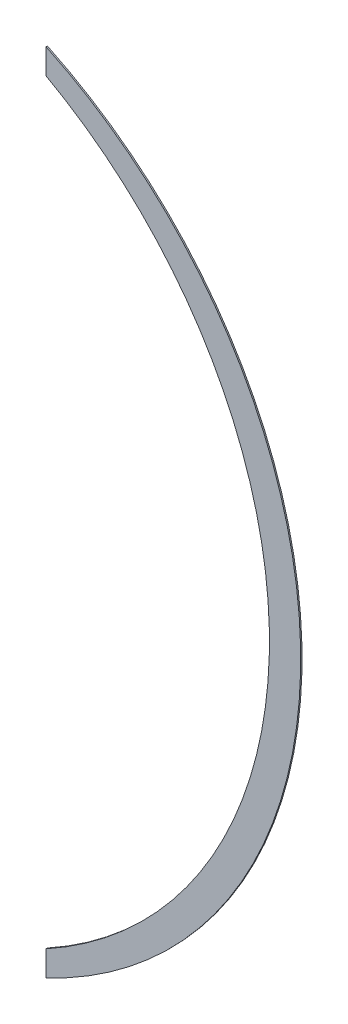
SolidWorks part; units mm, degrees
material "ASTM A36 Steel"
ref_plane "Front Plane" through (0, 0, 0) normal (0, 0, 1) x (1, 0, 0)
ref_plane "Top Plane" through (0, 0, 0) normal (0, 1, 0) x (1, 0, 0)
ref_plane "Right Plane" through (0, 0, 0) normal (1, 0, 0) x (0, 0, -1)
sketch "Sketch1" plane through (0, 0, 0) normal (0, 0, 1) x (1, 0, 0)
  line L0 (-194.5576, -430.1988) -> (-194.5576, -401.8695)
  line L1 (-194.5576, 444.3372) -> (-194.5576, 472.6665)
  arc A0 (-194.5576, -430.1988) -> (-194.5576, 472.6665) centre (-409.5194, 21.2339) ccw
  arc A1 (-194.5576, -401.8695) -> (-194.5576, 444.3372) centre (-427.5224, 21.2339) ccw
  dimension "D1" = 483
  dimension "D2" = 500
  dimension "D3" = 902.8653
extrude "Boss-Extrude1" add sketch "Sketch1" along normal blind 1.5
